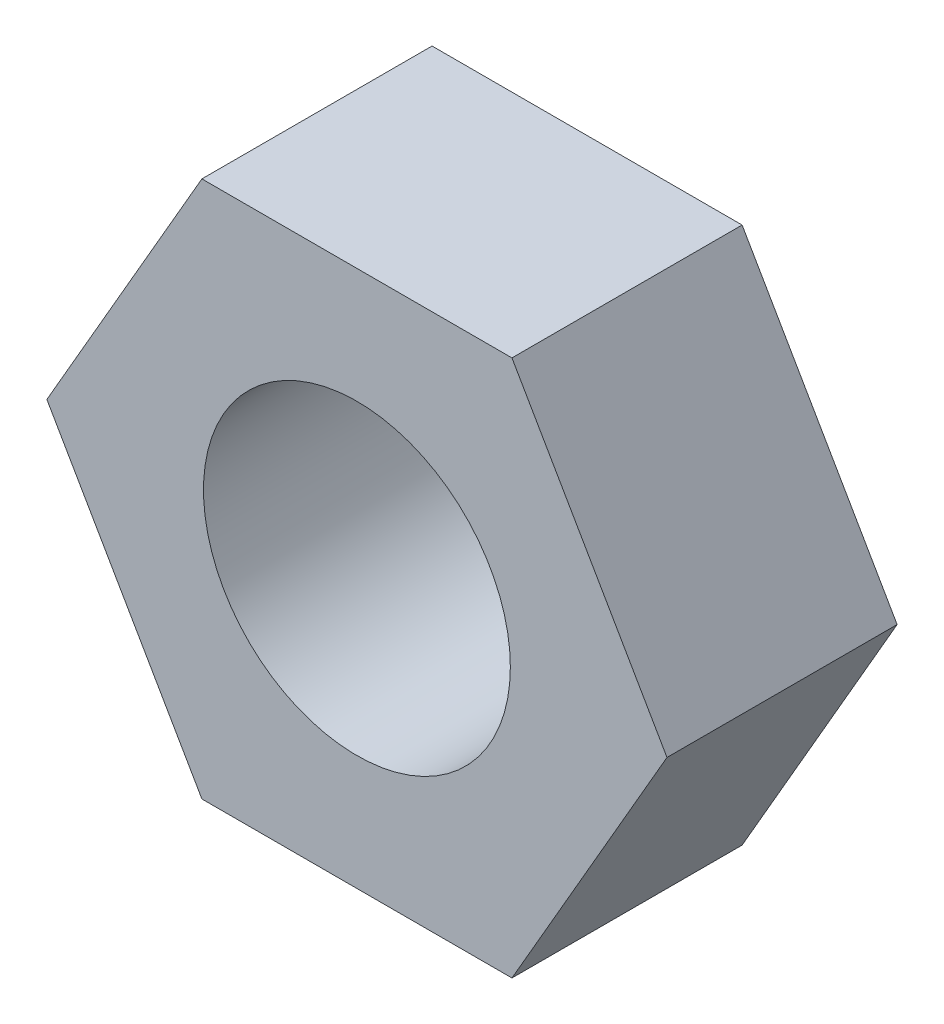
SolidWorks part; units mm, degrees
ref_plane "Front Plane" through (0, 0, 0) normal (0, 0, 1) x (1, 0, 0)
ref_plane "Top Plane" through (0, 0, 0) normal (0, 1, 0) x (1, 0, 0)
ref_plane "Right Plane" through (0, 0, 0) normal (1, 0, 0) x (0, 0, -1)
sketch "Sketch1" plane through (0, 0, 0) normal (0, 0, 1) x (1, 0, 0)
  line L1 (-4.0415, 0) -> (-2.0207, -3.5)
  line L2 (-2.0207, -3.5) -> (2.0207, -3.5)
  line L3 (2.0207, -3.5) -> (4.0415, 0)
  line L4 (4.0415, 0) -> (2.0207, 3.5)
  line L5 (2.0207, 3.5) -> (-2.0207, 3.5)
  line L6 (-2.0207, 3.5) -> (-4.0415, 0)
  circle A0 centre (0, 0) radius 2
  circle A2 centre (0, 0) radius 3.5 construction
  dimension "D1" = 4
  dimension "D2" = 7
extrude "Boss-Extrude1" add sketch "Sketch1" along normal blind 3
